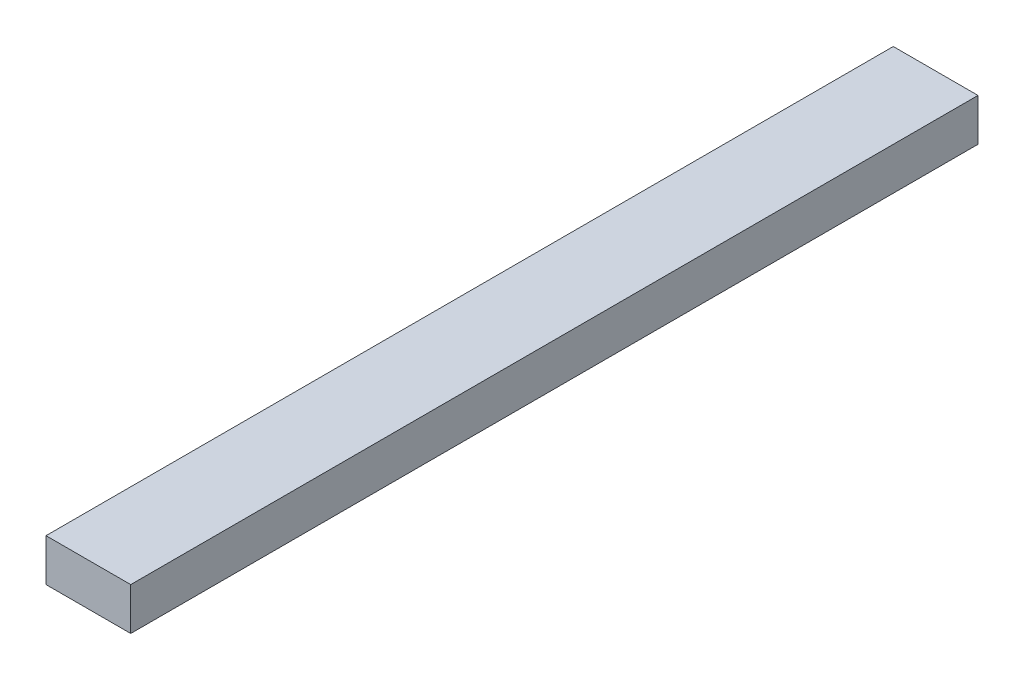
SolidWorks part; units mm, degrees
ref_plane "Front Plane" through (0, 0, 0) normal (0, 0, 1) x (1, 0, 0)
ref_plane "Top Plane" through (0, 0, 0) normal (0, 1, 0) x (1, 0, 0)
ref_plane "Right Plane" through (0, 0, 0) normal (1, 0, 0) x (0, 0, -1)
sketch "Sketch1" plane through (0, 0, 0) normal (0, 0, 1) x (1, 0, 0)
  line L1 (0, 0) -> (101.6, 0)
  line L2 (0, 0) -> (0, 50.8)
  line L3 (0, 50.8) -> (101.6, 50.8)
  line L4 (101.6, 0) -> (101.6, 50.8)
  dimension "D1" = 101.6
  dimension "D2" = 50.8
extrude "Boss-Extrude1" add sketch "Sketch1" along normal blind 1016
